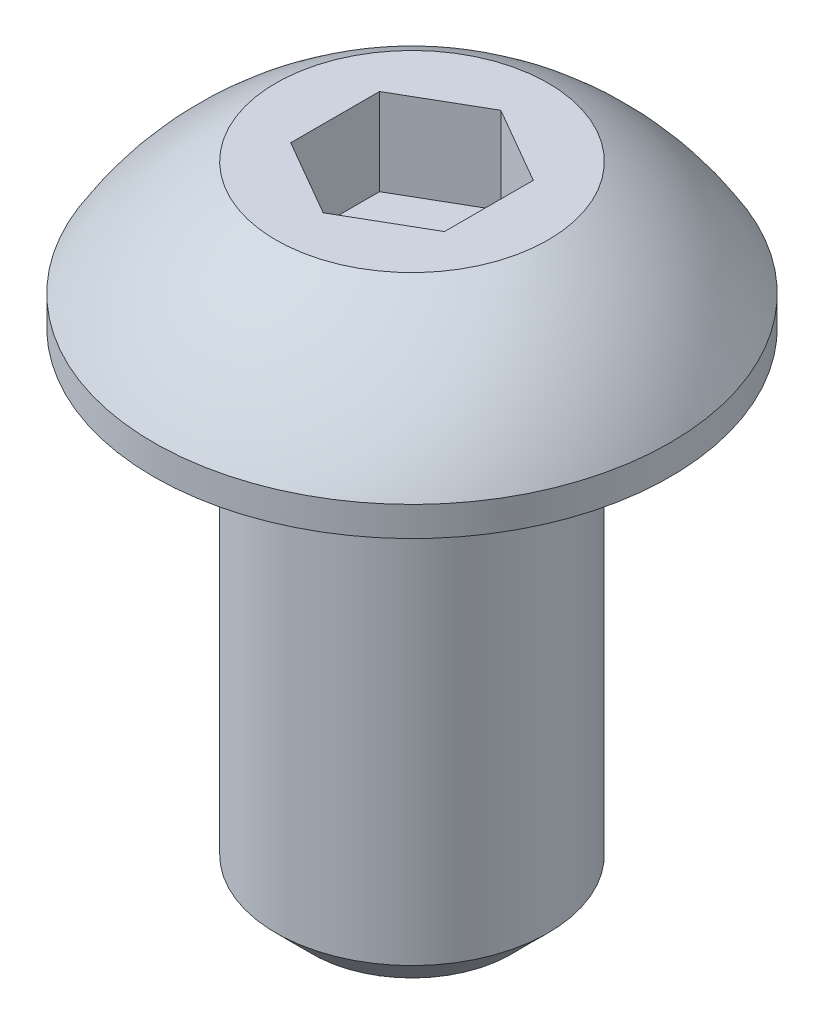
SolidWorks part; units mm, degrees
ref_plane "Front" through (0, 0, 0) normal (0, 0, 1) x (1, 0, 0)
ref_plane "Top" through (0, 0, 0) normal (0, 1, 0) x (1, 0, 0)
ref_plane "Right" through (0, 0, 0) normal (1, 0, 0) x (0, 0, -1)
sketch "Sketch1" plane through (0, 0, 0) normal (0, 0, 1) x (1, 0, 0)
  line L0 (0, 0) -> (3.3274, 0)
  line L1 (3.3274, 0) -> (3.3274, 0.381)
  line L2 (1.7526, 1.8542) -> (0, 1.8542)
  line L3 (0, 1.8542) -> (0, 0)
  line L4 (0, 0) -> (0, 100) construction
  arc A0 (3.3274, 0.381) -> (1.7526, 1.8542) centre (0, -1.5976) ccw
revolve "Base-Revolve" add sketch "Sketch1" angle 360 about L4
sketch "Sketch2" plane through (0, 0, 0) normal (0, 0, 1) x (1, 0, 0)
  line L0 (0, 0) -> (0, 100) construction
  line L1 (0, -6.35) -> (1.2802, -6.35)
  line L2 (1.2802, -6.35) -> (1.7526, -5.8776)
  line L3 (1.7526, -5.8776) -> (1.7526, 0)
  line L4 (1.7526, 0) -> (0, 0)
  line L5 (0, 0) -> (0, -6.35)
revolve "Boss-Revolve1" add sketch "Sketch2" angle 360 about L0
cosmetic thread "Cosmetic Thread1"
ref_plane "Plane4" through (0, 1.8542, 0) normal (0, 1, 0) x (-1, 0, 0)
sketch "Sketch3" plane through (0, 1.8542, 0) normal (0, 1, 0) x (-1, 0, 0)
  line L0 (0.9906, 0.5719) -> (0, 1.1438)
  line L1 (0, 1.1438) -> (-0.9906, 0.5719)
  line L2 (-0.9906, 0.5719) -> (-0.9906, -0.5719)
  line L3 (-0.9906, -0.5719) -> (0, -1.1438)
  line L4 (0, -1.1438) -> (0.9906, -0.5719)
  line L5 (0.9906, -0.5719) -> (0.9906, 0.5719)
extrude "Cut-Extrude1" cut sketch "Sketch3" against normal blind 1.1176
